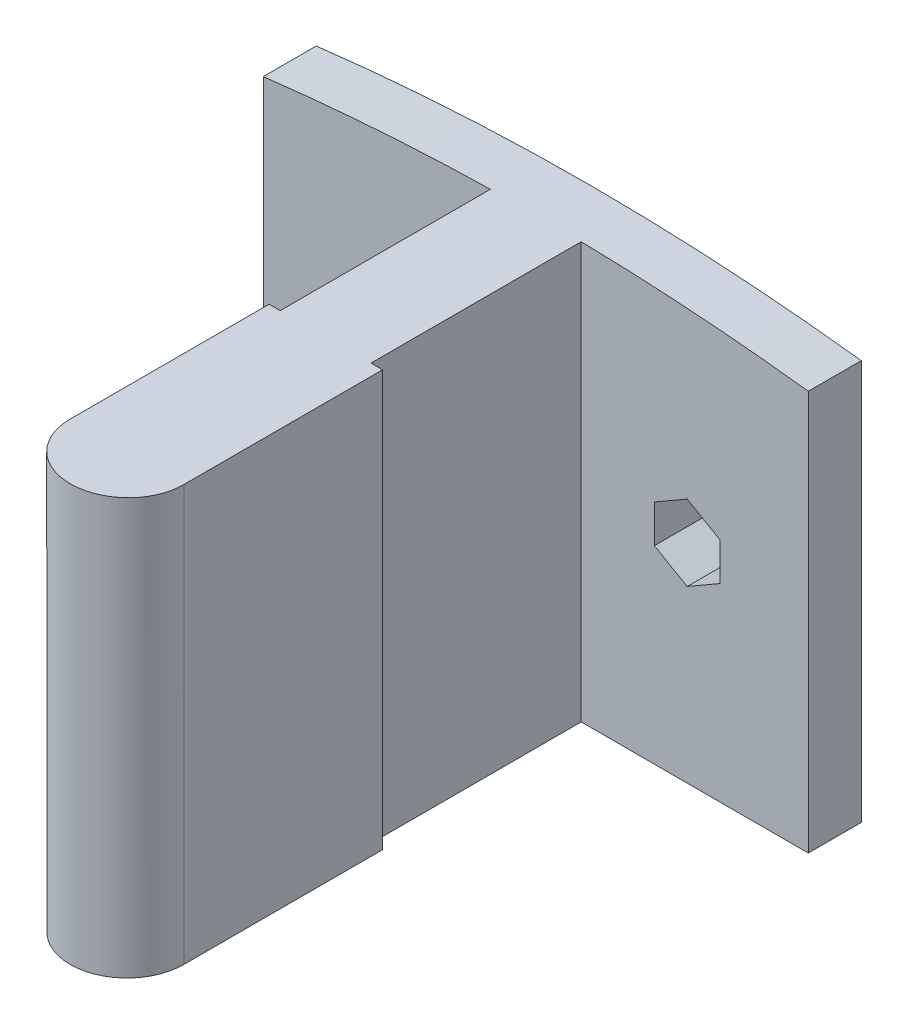
SolidWorks part; units mm, degrees
ref_plane "Front Plane" through (0, 0, 0) normal (0, 0, 1) x (1, 0, 0)
ref_plane "Top Plane" through (0, 0, 0) normal (0, 1, 0) x (1, 0, 0)
ref_plane "Right Plane" through (0, 0, 0) normal (1, 0, 0) x (0, 0, -1)
sketch "Sketch1" plane through (0, 0, 0) normal (0, 1, 0) x (1, 0, 0)
  line L0 (0, 0) -> (0, 12)
  line L1 (0, 12) -> (-6, 12)
  line L2 (-6, 12) -> (-6, 14)
  line L3 (-6, 14) -> (9, 14)
  line L4 (9, 14) -> (9, 12)
  line L5 (9, 12) -> (3, 12)
  line L6 (3, 12) -> (3, 0)
  line L7 (3, 0) -> (0, 0)
  dimension "D1" = 2
  dimension "D2" = 12
  dimension "D3" = 15
  dimension "D4" = 3
extrude "Boss-Extrude1" add sketch "Sketch1" along normal blind 11
sketch "Sketch3" plane through (0, 0, -14) normal (0, 0, -1) x (-1, 0, 0)
  line L0 (-9, 0) -> (6, 0) construction
  line L4 (-9, 11) -> (-9, 0) construction
  line L5 (6, 11) -> (6, 0) construction
  line L6 (-9, 11) -> (6, 11) construction
  line L7 (-9, 10.5294) -> (-9, 11)
  line L8 (-9, 11) -> (6, 11)
  line L9 (6, 11) -> (6, 10.5294)
  arc A0 (6, 10.5294) -> (-9, 10.5294) centre (-1.5, -49) ccw
  point P5 (-1.5, 0)
  line M6 (6, 0) -> (6, 11)
  line M7 (6, 11) -> (-9, 11)
  line M8 (-9, 11) -> (-9, 0)
  dimension "D1" = 60
extrude "Cut-Extrude1" cut sketch "Sketch3" against normal through all contours A0 L8 M8 | A0 M6 M7
sketch "Sketch4" plane through (0, 0, -12) normal (0, 0, 1) x (1, 0, 0)
  line L0 (-6, 0) -> (0, 0) construction
  line L2 (0, 10.9812) -> (0, 0) construction
  line L3 (-2.5, 6.5) -> (-3.366, 6)
  line L4 (-3.366, 6) -> (-3.366, 5)
  line L5 (-3.366, 5) -> (-2.5, 4.5)
  line L6 (-2.5, 4.5) -> (-1.634, 5)
  line L7 (-1.634, 5) -> (-1.634, 6)
  line L8 (-1.634, 6) -> (-2.5, 6.5)
  line L9 (5.5, 6.5) -> (4.634, 6)
  line L10 (4.634, 6) -> (4.634, 5)
  line L11 (4.634, 5) -> (5.5, 4.5)
  line L12 (5.5, 4.5) -> (6.366, 5)
  line L13 (6.366, 5) -> (6.366, 6)
  line L14 (6.366, 6) -> (5.5, 6.5)
  line L15 (3, 10.9812) -> (3, 0) construction
  circle A0 centre (-2.5, 5.5) radius 1 construction
  circle A1 centre (5.5, 5.5) radius 1 construction
  circle A2 centre (-2.5, 5.5) radius 0.866 construction
  circle A3 centre (5.5, 5.5) radius 0.866 construction
  point P25 (0, 0)
  point P26 (0, 0)
  dimension "D1" = 2
  dimension "D2" = 5.5
  dimension "D3" = 2.5
  dimension "D4" = 2.5
extrude "Cut-Extrude2" cut sketch "Sketch4" against normal through all
sketch "Sketch7" plane through (0, 0, 0) normal (0, -1, 0) x (1, 0, 0)
  line L0 (0, 0) -> (3, 0) construction
  line L1 (3, 0) -> (3, -1.5)
  line L2 (3, 0) -> (3, -12) construction
  line L3 (3, 0) -> (0, 0)
  line L4 (0, 0) -> (0, -1.5)
  line L5 (0, -12) -> (0, 0) construction
  arc A0 (3, -1.5) -> (0, -1.5) centre (1.5, -1.5) ccw
  point P5 (1.5, 0)
  line M2 (3, 0) -> (0, 0)
  line M3 (0, 0) -> (0, -12)
  line M9 (3, -12) -> (3, 0)
  dimension "D1" = 3
extrude "Cut-Extrude3" cut sketch "Sketch7" against normal through all contours A0 L3 M3 | A0 M9 M2
sketch "Sketch8" plane through (0, 0, 0) normal (0, -1, 0) x (1, 0, 0)
  line L3 (3, -1.5) -> (3, -12) construction
  line L4 (0.3, -6.75) -> (0, -6.75)
  line L5 (0, -12) -> (0, -1.5) construction
  line L6 (0, -6.75) -> (0, -12)
  line L7 (0, -12) -> (-6, -12)
  line L8 (-6, -12) -> (-6, -14)
  line L9 (-6, -14) -> (9, -14)
  line L10 (9, -14) -> (9, -12)
  line L11 (9, -12) -> (3, -12)
  line L12 (3, -12) -> (3, -6.75)
  line L13 (3, -6.75) -> (2.7, -6.75)
  line L14 (2.7, -12.3) -> (2.7, -1.5)
  line L15 (0.3, -1.5) -> (0.3, -12.3)
  line L16 (0.3, -12.3) -> (-5.7, -12.3)
  line L17 (-5.7, -12.3) -> (-5.7, -13.7)
  line L18 (-5.7, -13.7) -> (8.7, -13.7)
  line L19 (8.7, -13.7) -> (8.7, -12.3)
  line L20 (8.7, -12.3) -> (2.7, -12.3)
  line L21 (2.7, -12.3) -> (2.7, -6.75)
  line L22 (0.3, -6.75) -> (0.3, -12.3)
  line L23 (0.3, -12.3) -> (-5.7, -12.3)
  line L24 (-5.7, -12.3) -> (-5.7, -13.7)
  line L25 (-5.7, -13.7) -> (8.7, -13.7)
  line L26 (8.7, -13.7) -> (8.7, -12.3)
  line L27 (8.7, -12.3) -> (2.7, -12.3)
  arc A2 (2.7, -1.5) -> (0.3, -1.5) centre (1.5, -1.5) ccw
  point P3 (3, -6.75)
  dimension "D1" = 0.3
extrude "Cut-Extrude4" cut sketch "Sketch8" against normal through all
